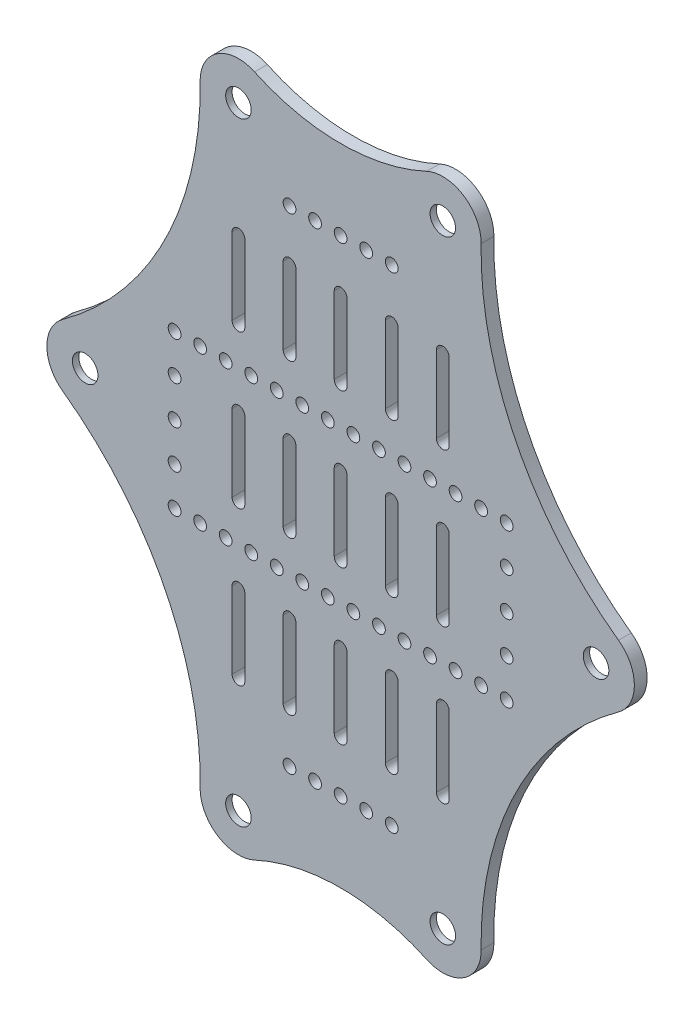
SolidWorks part; units mm, degrees
ref_plane "前视基准面" through (0, 0, 0) normal (0, 0, 1) x (1, 0, 0)
ref_plane "上视基准面" through (0, 0, 0) normal (0, 1, 0) x (1, 0, 0)
ref_plane "右视基准面" through (0, 0, 0) normal (1, 0, 0) x (0, 0, -1)
other "Configuration Table"
sketch "Sketch1" plane through (0, 0, 0) normal (0, 0, 1) x (1, 0, 0)
  line L0 (0, 0) -> (0, 120) construction
  line L1 (0, 120) -> (40, 120) construction
  line L2 (0, 0) -> (100, 0) construction
  circle A1 centre (100, 0) radius 15
  circle A2 centre (40, 120) radius 15
  circle A3 centre (-100, 0) radius 15
  circle A4 centre (-40, 120) radius 15
  circle A5 centre (40, -120) radius 15
  circle A6 centre (-40, -120) radius 15
  arc A7 (-33.6842, 133.6055) -> (33.6842, 133.6055) centre (0, 206.1684) ccw
  arc A8 (-33.6842, -133.6055) -> (33.6842, -133.6055) centre (0, -206.1684) cw
  arc A9 (-108.7909, 12.154) -> (-54.9978, 119.7403) centre (-184.9783, 117.4891) ccw
  arc A10 (108.7909, 12.154) -> (54.9978, 119.7403) centre (184.9783, 117.4891) cw
  arc A11 (108.7909, -12.154) -> (54.9978, -119.7403) centre (184.9783, -117.4891) ccw
  arc A12 (-108.7909, -12.154) -> (-54.9978, -119.7403) centre (-184.9783, -117.4891) cw
  dimension "D1" = 30
  dimension "D2" = 30
  dimension "D6" = 80
  dimension "D7" = 130
  dimension "D3" = 40
  dimension "D4" = 100
  dimension "D5" = 120
extrude "Boss-Extrude1" add sketch "Sketch1" along normal blind 5 contours A3 A12 A6 A8 A5 A11 A1 A10 A2 A7 A4 A9 | A3 | A4 | A2 | A1 | A5 | A6 A7
sketch "Sketch2" plane through (0, 0, 0) normal (0, 0, -1) x (-1, 0, 0)
  line L0 (0, 0) -> (0, 91.5521) construction
  line L1 (0, 0) -> (39.9574, 0) construction
  circle A0 centre (-40, 120) radius 5
  circle A1 centre (-100, 0) radius 5
  circle A2 centre (100, 0) radius 5
  circle A3 centre (40, 120) radius 5
  circle A4 centre (40, -120) radius 5
  circle A5 centre (-40, -120) radius 5
  dimension "D1" = 10
extrude "Cut-Extrude1" cut sketch "Sketch2" against normal through all
sketch "Sketch5" plane through (0, 0, 0) normal (0, 0, -1) x (-1, 0, 0)
  line L0 (0, 95) -> (0, 126.1684) construction
  line L1 (0, 95) -> (20, 95) construction
  line L2 (0, -95) -> (0, -126.1684) construction
  line L3 (0, 0) -> (50.0339, 0) construction
  line L5 (0, -95) -> (20, -95) construction
  circle A0 centre (20, 95) radius 2.5
  circle A1 centre (0, 95) radius 2.5
  circle A2 centre (10, 95) radius 2.5
  circle A17 centre (10, -95) radius 2.5
  circle A18 centre (0, -95) radius 2.5
  circle A19 centre (20, -95) radius 2.5
  arc A20 (-33.6842, 133.6055) -> (33.6842, 133.6055) centre (0, 206.1684) ccw construction
  circle A21 centre (-20, 95) radius 2.5
  circle A22 centre (-10, 95) radius 2.5
  arc A23 (33.6842, -133.6055) -> (-33.6842, -133.6055) centre (0, -206.1684) ccw construction
  circle A24 centre (-20, -95) radius 2.5
  circle A25 centre (-10, -95) radius 2.5
  dimension "D1" = 5
  dimension "D2" = 5
  dimension "D4" = 5
  dimension "D3" = 95
  dimension "D5" = 10
extrude "Cut-Extrude4" cut sketch "Sketch5" against normal blind 12.5
sketch "Sketch6" plane through (0, 0, 5) normal (0, 0, 1) x (1, 0, 0)
  line L110 (0, 0) -> (0, 75) construction
  line L111 (0, 75) -> (40, 75) construction
  line L112 (40, 75) -> (40, 45) construction
  line L113 (42.5, 75) -> (42.5, 45)
  line L114 (37.5, 75) -> (37.5, 45)
  line L115 (20, 75) -> (20, 45) construction
  line L116 (22.5, 75) -> (22.5, 45)
  line L117 (17.5, 75) -> (17.5, 45)
  line L118 (0, 75) -> (0, 45) construction
  line L119 (2.5, 75) -> (2.5, 45)
  line L120 (-2.5, 75) -> (-2.5, 45)
  line L121 (-20, 75) -> (-20, 45) construction
  line L122 (-17.5, 75) -> (-17.5, 45)
  line L123 (-22.5, 75) -> (-22.5, 45)
  line L124 (-40, 75) -> (-40, 45) construction
  line L125 (-37.5, 75) -> (-37.5, 45)
  line L126 (-42.5, 75) -> (-42.5, 45)
  line L127 (40, 120) -> (0, 120) construction
  line L128 (0, 15) -> (40, 15) construction
  line L129 (40, 15) -> (40, -15) construction
  line L130 (42.5, 15) -> (42.5, -15)
  line L131 (37.5, 15) -> (37.5, -15)
  line L132 (20, 15) -> (20, -15) construction
  line L133 (22.5, 15) -> (22.5, -15)
  line L134 (17.5, 15) -> (17.5, -15)
  line L135 (0, 15) -> (0, -15) construction
  line L136 (2.5, 15) -> (2.5, -15)
  line L137 (-2.5, 15) -> (-2.5, -15)
  line L138 (-20, 15) -> (-20, -15) construction
  line L139 (-17.5, 15) -> (-17.5, -15)
  line L140 (-22.5, 15) -> (-22.5, -15)
  line L141 (-40, 15) -> (-40, -15) construction
  line L142 (-37.5, 15) -> (-37.5, -15)
  line L143 (-42.5, 15) -> (-42.5, -15)
  line L144 (0, -45) -> (40, -45) construction
  line L145 (40, -45) -> (40, -75) construction
  line L146 (42.5, -45) -> (42.5, -75)
  line L147 (37.5, -45) -> (37.5, -75)
  line L148 (20, -45) -> (20, -75) construction
  line L149 (22.5, -45) -> (22.5, -75)
  line L150 (17.5, -45) -> (17.5, -75)
  line L151 (0, -45) -> (0, -75) construction
  line L152 (2.5, -45) -> (2.5, -75)
  line L153 (-2.5, -45) -> (-2.5, -75)
  line L154 (-20, -45) -> (-20, -75) construction
  line L155 (-17.5, -45) -> (-17.5, -75)
  line L156 (-22.5, -45) -> (-22.5, -75)
  line L157 (-40, -45) -> (-40, -75) construction
  line L158 (-37.5, -45) -> (-37.5, -75)
  line L159 (-42.5, -45) -> (-42.5, -75)
  arc A90 (42.5, 75) -> (37.5, 75) centre (40, 75) ccw
  arc A91 (37.5, 45) -> (42.5, 45) centre (40, 45) ccw
  arc A92 (22.5, 75) -> (17.5, 75) centre (20, 75) ccw
  arc A93 (17.5, 45) -> (22.5, 45) centre (20, 45) ccw
  arc A94 (2.5, 75) -> (-2.5, 75) centre (0, 75) ccw
  arc A95 (-2.5, 45) -> (2.5, 45) centre (0, 45) ccw
  arc A96 (-17.5, 75) -> (-22.5, 75) centre (-20, 75) ccw
  arc A97 (-22.5, 45) -> (-17.5, 45) centre (-20, 45) ccw
  arc A98 (-37.5, 75) -> (-42.5, 75) centre (-40, 75) ccw
  arc A99 (-42.5, 45) -> (-37.5, 45) centre (-40, 45) ccw
  arc A100 (42.5, 15) -> (37.5, 15) centre (40, 15) ccw
  arc A101 (37.5, -15) -> (42.5, -15) centre (40, -15) ccw
  arc A102 (22.5, 15) -> (17.5, 15) centre (20, 15) ccw
  arc A103 (17.5, -15) -> (22.5, -15) centre (20, -15) ccw
  arc A104 (2.5, 15) -> (-2.5, 15) centre (0, 15) ccw
  arc A105 (-2.5, -15) -> (2.5, -15) centre (0, -15) ccw
  arc A106 (-17.5, 15) -> (-22.5, 15) centre (-20, 15) ccw
  arc A107 (-22.5, -15) -> (-17.5, -15) centre (-20, -15) ccw
  arc A108 (-37.5, 15) -> (-42.5, 15) centre (-40, 15) ccw
  arc A109 (-42.5, -15) -> (-37.5, -15) centre (-40, -15) ccw
  arc A110 (42.5, -45) -> (37.5, -45) centre (40, -45) ccw
  arc A111 (37.5, -75) -> (42.5, -75) centre (40, -75) ccw
  arc A112 (22.5, -45) -> (17.5, -45) centre (20, -45) ccw
  arc A113 (17.5, -75) -> (22.5, -75) centre (20, -75) ccw
  arc A114 (2.5, -45) -> (-2.5, -45) centre (0, -45) ccw
  arc A115 (-2.5, -75) -> (2.5, -75) centre (0, -75) ccw
  arc A116 (-17.5, -45) -> (-22.5, -45) centre (-20, -45) ccw
  arc A117 (-22.5, -75) -> (-17.5, -75) centre (-20, -75) ccw
  arc A118 (-37.5, -45) -> (-42.5, -45) centre (-40, -45) ccw
  arc A119 (-42.5, -75) -> (-37.5, -75) centre (-40, -75) ccw
  point P115 (40, 60)
  point P123 (20, 60)
  point P130 (0, 60)
  point P137 (-20, 60)
  point P144 (-40, 60)
  point P153 (40, 0)
  point P160 (20, 0)
  point P167 (0, 0)
  point P174 (-20, 0)
  point P181 (-40, 0)
  point P189 (40, -60)
  point P196 (20, -60)
  point P203 (0, -60)
  point P210 (-20, -60)
  point P217 (-40, -60)
  dimension "D9" = 2.5
  dimension "D7" = 40
  dimension "D8" = 75
  dimension "D10" = 30
  dimension "D11" = 20
  dimension "D12" = 60
  dimension "D13" = 20
extrude "Cut-Extrude5" cut sketch "Sketch6" against normal blind 10
sketch "Sketch7" plane through (0, 0, 5) normal (0, 0, 1) x (1, 0, 0)
  line L4 (0, 0) -> (0, 30) construction
  line L5 (0, 30) -> (-65, 30) construction
  line L6 (0, 0) -> (85, 0) construction
  line L7 (0, -30) -> (-65, -30) construction
  circle A28 centre (-65, 30) radius 2.5
  circle A29 centre (-55, 30) radius 2.5
  circle A30 centre (-45, 30) radius 2.5
  circle A31 centre (-35, 30) radius 2.5
  circle A32 centre (-25, 30) radius 2.5
  circle A33 centre (-15, 30) radius 2.5
  circle A34 centre (-5, 30) radius 2.5
  circle A35 centre (5, 30) radius 2.5
  circle A36 centre (15, 30) radius 2.5
  circle A37 centre (25, 30) radius 2.5
  circle A38 centre (35, 30) radius 2.5
  circle A39 centre (45, 30) radius 2.5
  circle A40 centre (55, 30) radius 2.5
  circle A41 centre (65, 30) radius 2.5
  circle A42 centre (65, -30) radius 2.5
  circle A43 centre (55, -30) radius 2.5
  circle A44 centre (45, -30) radius 2.5
  circle A45 centre (35, -30) radius 2.5
  circle A46 centre (25, -30) radius 2.5
  circle A47 centre (15, -30) radius 2.5
  circle A48 centre (5, -30) radius 2.5
  circle A49 centre (-5, -30) radius 2.5
  circle A50 centre (-15, -30) radius 2.5
  circle A51 centre (-25, -30) radius 2.5
  circle A52 centre (-35, -30) radius 2.5
  circle A53 centre (-45, -30) radius 2.5
  circle A54 centre (-55, -30) radius 2.5
  circle A55 centre (-65, -30) radius 2.5
  dimension "D5" = 5
  dimension "D6" = 30
  dimension "D7" = 65
  dimension "D8" = 10
extrude "Cut-Extrude6" cut sketch "Sketch7" against normal blind 10
sketch "Sketch8" plane through (0, 0, 5) normal (0, 0, 1) x (1, 0, 0)
  line L5 (0, 0) -> (-65, 0) construction
  line L6 (-65, 0) -> (-40, 15) construction
  line L7 (-40, 15) -> (-65, 15) construction
  line L8 (-65, 15) -> (-65, 0) construction
  line L9 (0, 0) -> (0, 17.5) construction
  circle A6 centre (-65, 0) radius 2.5
  circle A7 centre (-65, 15) radius 2.5
  circle A8 centre (-65, -15) radius 2.5
  circle A9 centre (65, -15) radius 2.5
  circle A10 centre (65, 0) radius 2.5
  circle A11 centre (65, 15) radius 2.5
  dimension "D4" = 5
  dimension "D6" = 5
  dimension "D5" = 65
extrude "Cut-Extrude7" cut sketch "Sketch8" against normal blind 10
sketch "Sketch9" plane through (0, 0, 0) normal (0, 0, -1) x (-1, 0, 0)
  circle A1 centre (100, 0) radius 8.75
  circle A2 centre (40, 120) radius 8.75
  circle A3 centre (40, -120) radius 8.75
  circle A4 centre (-40, -120) radius 8.75
  circle A5 centre (-100, 0) radius 8.75
  circle A6 centre (-40, 120) radius 8.75
  dimension "D1" = 17.5
extrude "Cut-Extrude8" cut sketch "Sketch9" against normal blind 2.5
sketch "Sketch10" plane through (0, 0, 5) normal (0, 0, 1) x (1, 0, 0)
  line L0 (-115, 0) -> (115, 0)
  line L2 (-115, -135) -> (115, -135)
  line L3 (-115, -135) -> (-115, 135)
  line L4 (-115, 135) -> (115, 135)
  line L5 (115, -135) -> (115, 135)
  line L6 (-115, -135) -> (115, 135) construction
  line L7 (-115, 135) -> (115, -135) construction
  arc A0 (-108.7909, 12.154) -> (-108.7909, -12.154) centre (-100, 0) ccw construction
  arc A1 (108.7909, -12.154) -> (108.7909, 12.154) centre (100, 0) ccw construction
  point P8 (0, 0)
  dimension "D1" = 270
  dimension "D2" = 230
extrude "Cut-Extrude9" [suppressed] cut sketch "Sketch10" against normal blind 10 contours L0 L5 L4 L3
